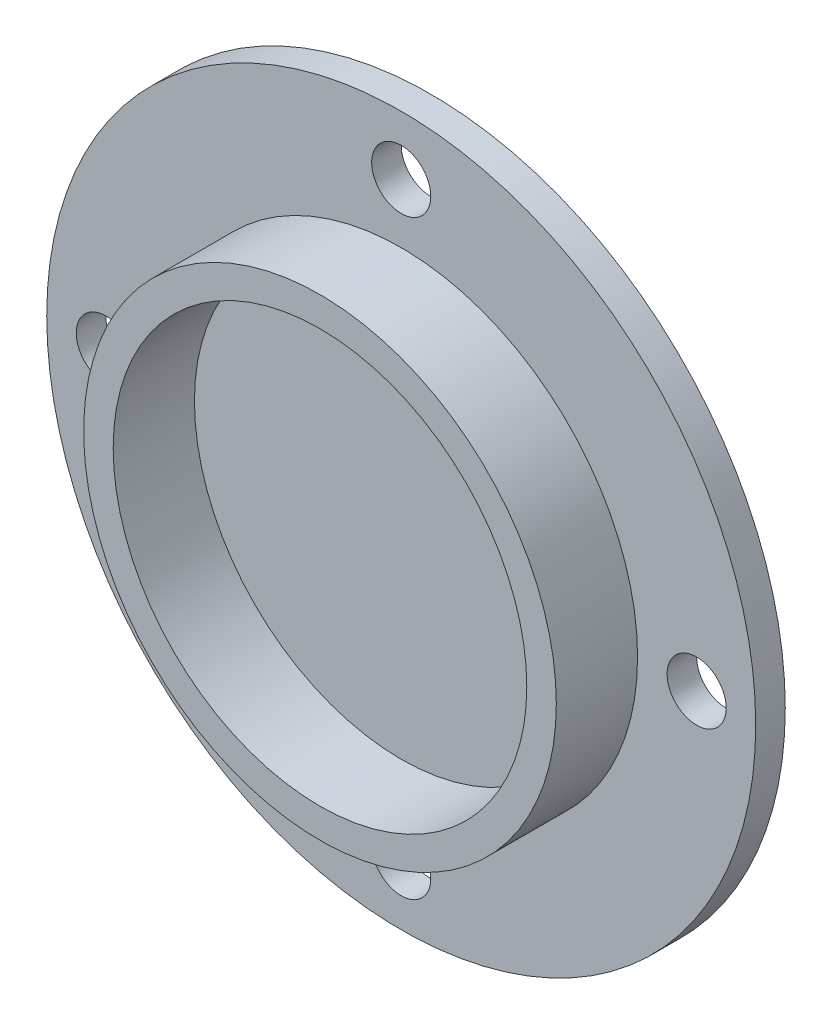
SolidWorks part; units mm, degrees
ref_plane "前视" through (0, 0, 0) normal (0, 0, 1) x (1, 0, 0)
ref_plane "上视" through (0, 0, 0) normal (0, 1, 0) x (1, 0, 0)
ref_plane "右视" through (0, 0, 0) normal (1, 0, 0) x (0, 0, -1)
sketch "草图1" plane through (0, 0, 0) normal (0, 0, 1) x (1, 0, 0)
  line L0 (0, 149.6675) -> (0, -153.1685) construction
  line L1 (-173.2992, 0) -> (179.7177, 0) construction
  circle A0 centre (0, 0) radius 120
  circle A1 centre (0, 0) radius 100 construction
  circle A2 centre (0, 100) radius 10
  circle A3 centre (-100, 0) radius 10
  circle A4 centre (100, 0) radius 10
  circle A5 centre (0, -100) radius 10
  dimension "D1" = 240
  dimension "D2" = 200
  dimension "D3" = 20
  dimension "D4" = 20
  dimension "D5" = 20
  dimension "D6" = 20
extrude "拉伸1" add sketch "草图1" along normal blind 10
sketch "草图2" plane through (0, 0, 10) normal (0, 0, 1) x (1, 0, 0)
  circle A0 centre (0, 0) radius 80
  circle A1 centre (0, 0) radius 70
  dimension "D1" = 160
  dimension "D2" = 140
extrude "拉伸2" add sketch "草图2" along normal blind 27.5
